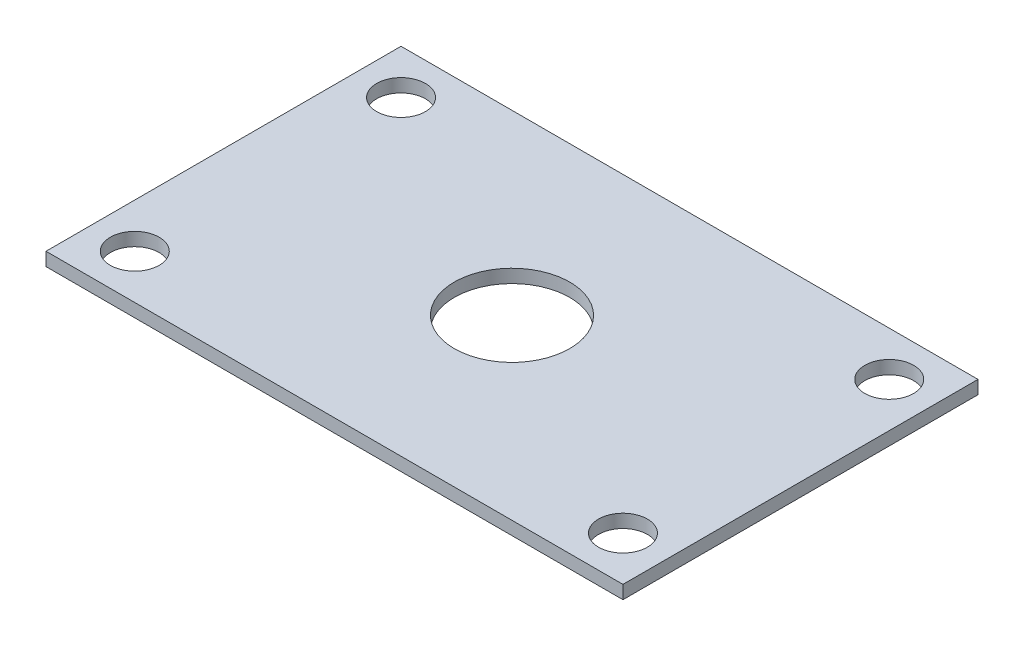
SolidWorks part; units mm, degrees
ref_plane "Alzado" through (0, 0, 0) normal (0, 0, 1) x (1, 0, 0)
ref_plane "Planta" through (0, 0, 0) normal (0, 1, 0) x (1, 0, 0)
ref_plane "Vista lateral" through (0, 0, 0) normal (1, 0, 0) x (0, 0, -1)
sketch "Croquis1" plane through (0, 0, 0) normal (0, 1, 0) x (1, 0, 0)
  line L1 (-65, 40) -> (65, 40)
  line L2 (-65, 40) -> (-65, -40)
  line L3 (-65, -40) -> (65, -40)
  line L4 (65, 40) -> (65, -40)
  line L5 (-65, 40) -> (65, -40) construction
  line L6 (-65, -40) -> (65, 40) construction
  point P0 (0, 0)
  dimension "D1" = 130
  dimension "D2" = 80
extrude "Saliente-Extruir1" add sketch "Croquis1" along normal blind 3
sketch "Croquis2" plane through (0, 3, 0) normal (0, 1, 0) x (1, 0, 0)
  circle A0 centre (0, 0) radius 13
  dimension "D1" = 26
extrude "Cortar-Extruir1" cut sketch "Croquis2" against normal blind 3
sketch "Croquis3" plane through (0, 3, 0) normal (0, 1, 0) x (1, 0, 0)
  line L0 (65, -40) -> (65, 40) construction
  line L1 (-65, 40) -> (-65, -40) construction
  line L2 (-65, -40) -> (65, -40) construction
  line L3 (65, 40) -> (-65, 40) construction
  circle A0 centre (-55, 30) radius 5.5
  circle A1 centre (-55, -30) radius 5.5
  circle A2 centre (55, 30) radius 5.5
  circle A3 centre (55, -30) radius 5.5
  dimension "D1" = 11
  dimension "D2" = 11
  dimension "D3" = 11
  dimension "D4" = 11
  dimension "D5" = 10
  dimension "D6" = 10
  dimension "D7" = 10
  dimension "D8" = 10
  dimension "D9" = 10
  dimension "D10" = 10
  dimension "D11" = 10
  dimension "D12" = 10
extrude "Cortar-Extruir2" cut sketch "Croquis3" against normal blind 3
